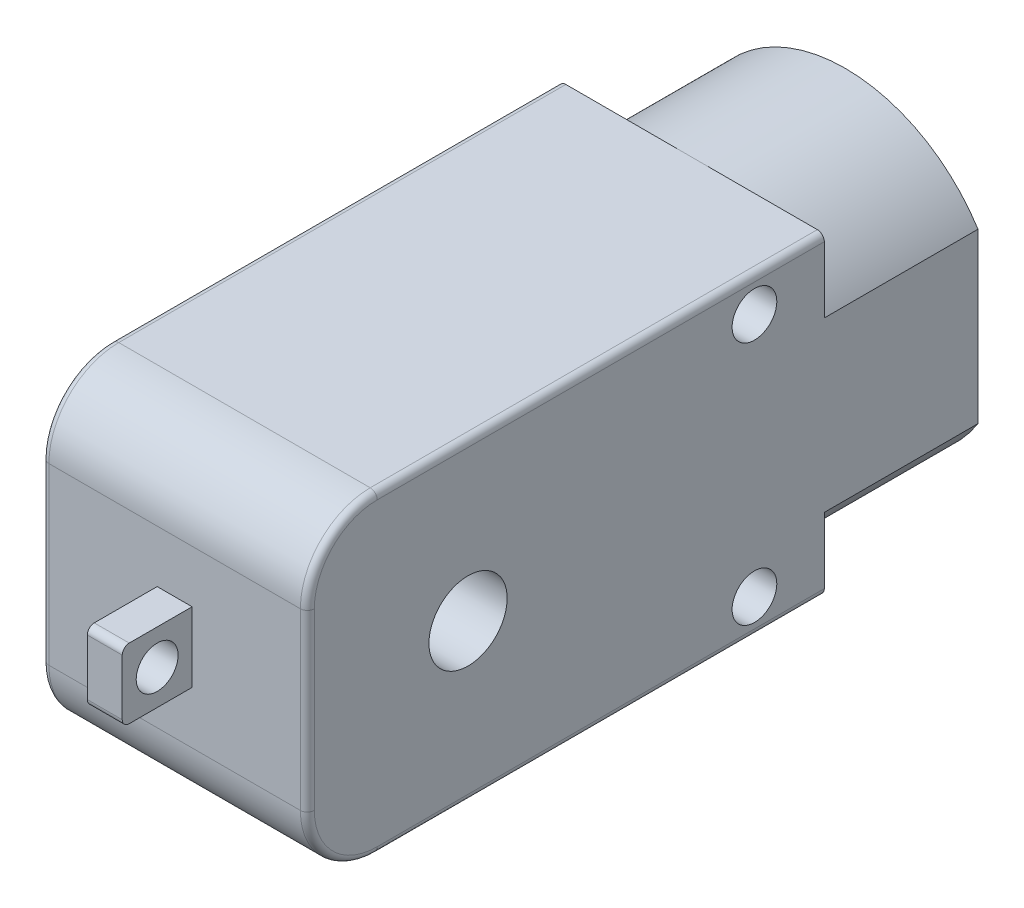
SolidWorks part; units mm, degrees
ref_plane "Front Plane" through (0, 0, 0) normal (0, 0, 1) x (1, 0, 0)
ref_plane "Top Plane" through (0, 0, 0) normal (0, 1, 0) x (1, 0, 0)
ref_plane "Right Plane" through (0, 0, 0) normal (1, 0, 0) x (0, 0, -1)
sketch "Sketch1" plane through (0, 0, 0) normal (0, 0, 1) x (1, 0, 0)
  line L1 (9.5, 11.25) -> (-9.5, 11.25)
  line L2 (9.5, 11.25) -> (9.5, -11.25)
  line L3 (9.5, -11.25) -> (-9.5, -11.25)
  line L4 (-9.5, 11.25) -> (-9.5, -11.25)
  line L5 (9.5, 11.25) -> (-9.5, -11.25) construction
  line L6 (9.5, -11.25) -> (-9.5, 11.25) construction
  point P0 (0, 0)
  dimension "D1" = 22.5
  dimension "D2" = 19
extrude "Boss-Extrude1" add sketch "Sketch1" along normal blind 37
sketch "Sketch2" plane through (0, 0, 0) normal (0, 0, -1) x (-1, 0, 0)
  line L0 (9.5, 6.026) -> (9.5, -6.026)
  line L1 (9.5, 11.25) -> (9.5, -11.25) construction
  line L2 (-9.5, 6.026) -> (-9.5, -6.026)
  arc A0 (9.5, 6.026) -> (-9.5, 6.026) centre (0, 0) ccw
  arc A1 (-9.5, -6.026) -> (9.5, -6.026) centre (0, 0) ccw
extrude "Boss-Extrude2" add sketch "Sketch2" along normal blind 11
fillet "Fillet1" radius 5 2 edges at (0, -11.25, 37) (0, 11.25, 37)
sketch "Sketch3" plane through (9.5, 0, 0) normal (1, 0, 0) x (0, 0, -1)
  circle A0 centre (-5, 8.75) radius 1.6
  circle A1 centre (-5, -8.75) radius 1.6
  dimension "D1" = 17.5
  dimension "D3" = 3.2
  dimension "D2" = 8.75
  dimension "D4" = 5
  dimension "D5" = 0
extrude "Cut-Extrude1" cut sketch "Sketch3" against normal through all
sketch "Sketch4" plane through (0, 0, 37) normal (0, 0, 1) x (1, 0, 0)
  line L1 (1.25, 2.5) -> (-1.25, 2.5)
  line L2 (1.25, 2.5) -> (1.25, -2.5)
  line L3 (1.25, -2.5) -> (-1.25, -2.5)
  line L4 (-1.25, 2.5) -> (-1.25, -2.5)
  line L5 (1.25, 2.5) -> (-1.25, -2.5) construction
  line L6 (1.25, -2.5) -> (-1.25, 2.5) construction
  point P0 (0, 0)
  dimension "D1" = 2.5
  dimension "D2" = 5
extrude "Boss-Extrude3" add sketch "Sketch4" along normal blind 5
fillet "Fillet2" radius 0.5 12 edges at (0, -2.5, 42) (0, 2.5, 42) (-9.5, -11.25, 16) (-9.5, -9.7855, 35.5355) (-9.5, 0, 37) (-9.5, 9.7855, 35.5355) (9.5, -11.25, 16) (9.5, -9.7855, 35.5355) (9.5, 0, 37) (9.5, 9.7855, 35.5355) (-9.5, 11.25, 16) (9.5, 11.25, 16)
sketch "Sketch5" plane through (1.25, 0, 0) normal (1, 0, 0) x (0, 0, -1)
  line L0 (-41.5, 2.5) -> (-37, 2.5) construction
  line L1 (-42, -2) -> (-42, 2) construction
  circle A0 centre (-39.5, 0) radius 1.5
  dimension "D1" = 3
  dimension "D2" = 2.5
  dimension "D3" = 2.5
extrude "Cut-Extrude2" cut sketch "Sketch5" against normal blind 5
sketch "Sketch6" plane through (9.5, 0, 0) normal (1, 0, 0) x (0, 0, -1)
  circle A0 centre (-25.5, 0) radius 2.8
  dimension "D1" = 5.6
  dimension "D2" = 25.5
extrude "Cut-Extrude3" cut sketch "Sketch6" against normal through all
sketch "Sketch7" plane through (0, 0, -11) normal (0, 0, -1) x (-1, 0, 0)
  line L4 (-8.3, 5.6668) -> (-8.3, -5.6668)
  line L5 (8.3, -5.6668) -> (8.3, 5.6668)
  line L6 (-8.3, 5.6668) -> (-8.3, -5.6668)
  line L7 (8.3, -5.6668) -> (8.3, 5.6668)
  arc A4 (8.3, 5.6668) -> (-8.3, 5.6668) centre (0, 0) ccw
  arc A5 (-8.3, -5.6668) -> (8.3, -5.6668) centre (0, 0) ccw
  arc A6 (8.3, 5.6668) -> (-8.3, 5.6668) centre (0, 0) ccw
  arc A7 (-8.3, -5.6668) -> (8.3, -5.6668) centre (0, 0) ccw
  dimension "D1" = 1.2
extrude "Cut-Extrude4" cut sketch "Sketch7" against normal blind 11
sketch "Sketch8" plane through (0, 0, 0) normal (0, 0, -1) x (-1, 0, 0)
  circle A0 centre (0, 0) radius 3
  dimension "D1" = 6
extrude "Cut-Extrude5" cut sketch "Sketch8" against normal blind 2
